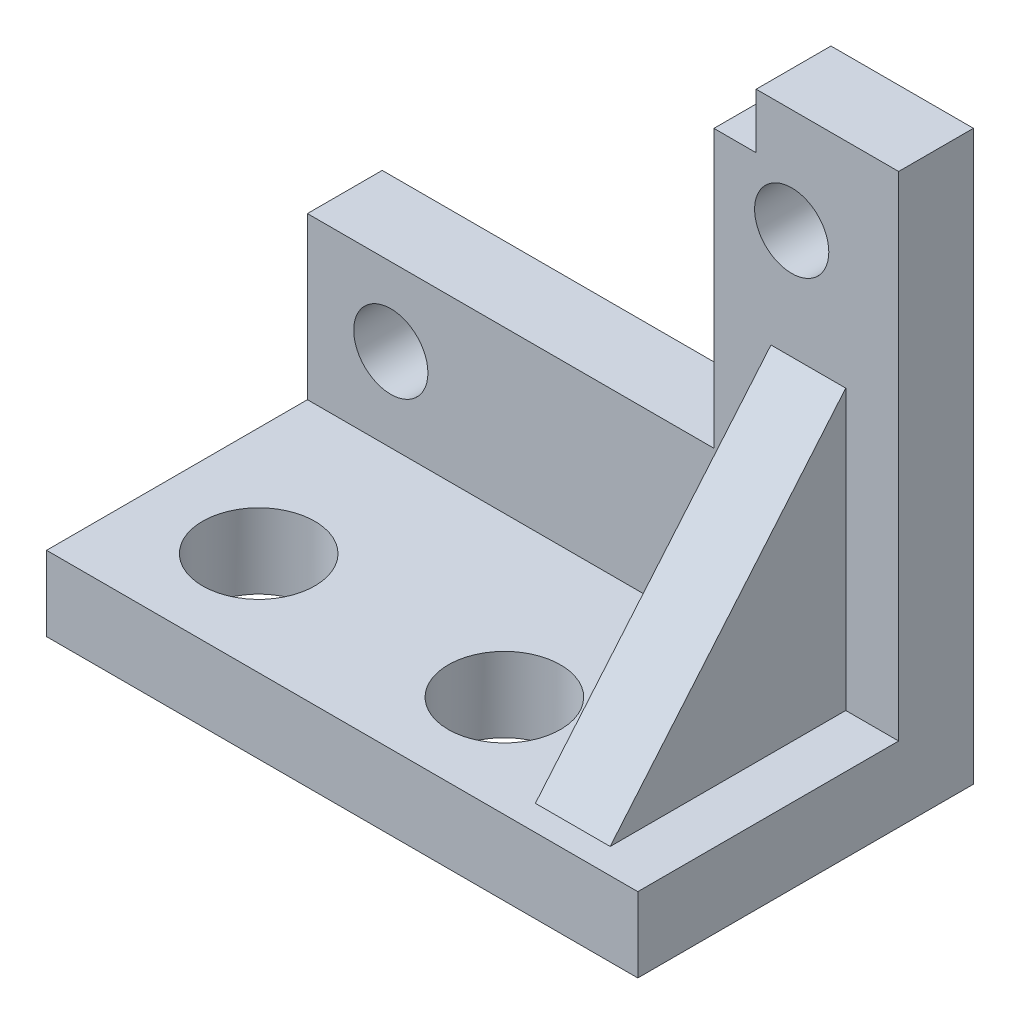
SolidWorks part; units mm, degrees
ref_plane "Front Plane" through (0, 0, 0) normal (0, 0, 1) x (1, 0, 0)
ref_plane "Top Plane" through (0, 0, 0) normal (0, 1, 0) x (1, 0, 0)
ref_plane "Right Plane" through (0, 0, 0) normal (1, 0, 0) x (0, 0, -1)
sketch "Sketch2" plane through (0, 0, 0) normal (0, 0, 1) x (1, 0, 0)
  line L0 (4.3952, 7.8274) -> (4.3952, -1.4384)
  line L1 (4.3952, -1.4384) -> (-11.8608, -1.4384)
  line L2 (-11.8608, -1.4384) -> (-11.8608, -8.2804)
  line L3 (-11.8608, -8.2804) -> (12.2372, -8.2804)
  line L4 (12.2372, -8.2804) -> (12.2372, 12.6586)
  line L5 (12.2372, 12.6586) -> (7.6972, 12.6586)
  line L7 (7.6972, 12.6586) -> (6.1882, 12.6586)
  line L8 (-11.8608, -1.4384) -> (-12.8608, -1.4384)
  line L9 (-11.8608, -1.4384) -> (-11.8608, -8.2804)
  line L10 (-11.8608, -8.2804) -> (-12.8608, -8.2804)
  line L11 (-12.8608, -1.4384) -> (-12.8608, -8.2804)
  line L12 (4.3952, 10.3218) -> (4.3952, 7.8274)
  line L13 (4.3952, 10.3218) -> (6.1882, 10.3218)
  line L14 (6.1882, 10.3218) -> (6.1882, 12.6586)
  circle A0 centre (7.6972, 8.2136) radius 1.5748
  circle A1 centre (-9.3208, -4.7404) radius 1.5748
  point P0 (6.4597, 9.1875)
  dimension "D5" = 16.494
  dimension "D1" = 1
  dimension "D2" = 6.842
  dimension "D3" = 20.939
  dimension "D4" = 24.098
  dimension "D6" = 2.54
  dimension "D7" = 3.54
  dimension "D8" = 17.018
extrude "Boss-Extrude1" add sketch "Sketch2" along normal blind 3.175 contours A0 | L3 L4 L5 L7 L14 L13 L12 L0 L1 L2 | A1
sketch "Sketch5" plane through (0, 0, 0) normal (0, 0, -1) x (-1, 0, 0)
  line L1 (-12.2372, -8.2804) -> (11.8608, -8.2804)
  line L2 (-12.2372, -8.2804) -> (-12.2372, -11.4554)
  line L3 (-12.2372, -11.4554) -> (11.8608, -11.4554)
  line L4 (11.8608, -8.2804) -> (11.8608, -11.4554)
  line L5 (11.8608, -1.4384) -> (11.8608, -8.2804) construction
  dimension "D1" = 3.175
extrude "Boss-Extrude2" add sketch "Sketch5" against normal blind 19.05
sketch "Sketch7" plane through (0, 0, 3.175) normal (0, 0, 1) x (1, 0, 0)
  line L0 (-11.8608, -1.4384) -> (-11.8608, -8.2804) construction
  line L1 (-11.8608, -1.4384) -> (-12.8608, -1.4384)
  line L2 (-11.8608, -1.4384) -> (-11.8608, -8.2804)
  line L3 (-11.8608, -8.2804) -> (-12.8608, -8.2804)
  line L4 (-12.8608, -1.4384) -> (-12.8608, -8.2804)
  dimension "D1" = 1
extrude "Boss-Extrude3" add sketch "Sketch7" against normal blind 3.175
sketch "Sketch8" plane through (0, 0, 19.05) normal (0, 0, 1) x (1, 0, 0)
  line L1 (-11.8608, -11.4554) -> (-12.8608, -11.4554)
  line L2 (-11.8608, -11.4554) -> (-11.8608, -8.2804)
  line L3 (-11.8608, -8.2804) -> (-12.8608, -8.2804)
  line L4 (-12.8608, -11.4554) -> (-12.8608, -8.2804)
extrude "Boss-Extrude4" add sketch "Sketch8" against normal blind 19.05
sketch "Sketch9" plane through (0, 0, 3.175) normal (0, 0, 1) x (1, 0, 0)
  line L0 (6.8165, -8.2804) -> (9.9915, -8.2804)
  line L1 (9.9915, -8.2804) -> (9.9915, 3.57)
  line L2 (-12.8608, -8.2804) -> (12.2372, -8.2804) construction
  line L3 (9.9915, 3.57) -> (6.8165, 3.57)
  line L4 (6.8165, 3.57) -> (6.8165, -8.2804)
  line L6 (12.2372, -8.2804) -> (12.2372, 12.6586) construction
  dimension "D1" = 3.175
  dimension "D2" = 2.2457
extrude "Boss-Extrude5" add sketch "Sketch9" along normal blind 10
sketch "Sketch10" plane through (9.9915, 0, 0) normal (1, 0, 0) x (0, 0, -1)
  line L0 (-3.175, 3.57) -> (-13.175, -8.2804)
  line L1 (-3.175, 3.57) -> (-13.175, 3.57)
  line L2 (-13.175, 3.57) -> (-13.175, -8.2804)
extrude "Cut-Extrude1" cut sketch "Sketch10" against normal through all
sketch "Sketch11" plane through (0, -8.2804, 0) normal (0, 1, 0) x (1, 0, 0)
  line L7 (-8.2367, -12.2485) -> (-8.2367, -14.2485)
  line L8 (-8.2367, -14.2485) -> (-14.967, -14.2485)
  line L9 (-8.2367, -14.2485) -> (13.7986, -14.2485)
  line L11 (-8.2367, -19.6992) -> (13.7986, -19.6992)
  line L12 (13.7986, -14.2485) -> (13.7986, -19.6992)
  line L13 (-14.967, -14.2485) -> (-14.967, -19.6992)
  line L14 (-14.967, -19.6992) -> (-8.2367, -19.6992)
  circle A0 centre (-8.2367, -9.8673) radius 2.3813
  circle A1 centre (2.2559, -9.9305) radius 2.3813
  line M4 (-12.8608, -3.175) -> (-12.8608, -19.05)
  line M5 (-12.8608, -19.05) -> (12.2372, -19.05)
  line M6 (12.2372, -19.05) -> (12.2372, -3.175)
extrude "Cut-Extrude5" cut sketch "Sketch11" against normal blind 10 contours A0 | L9 L8 M4 M5 M6 | A1
